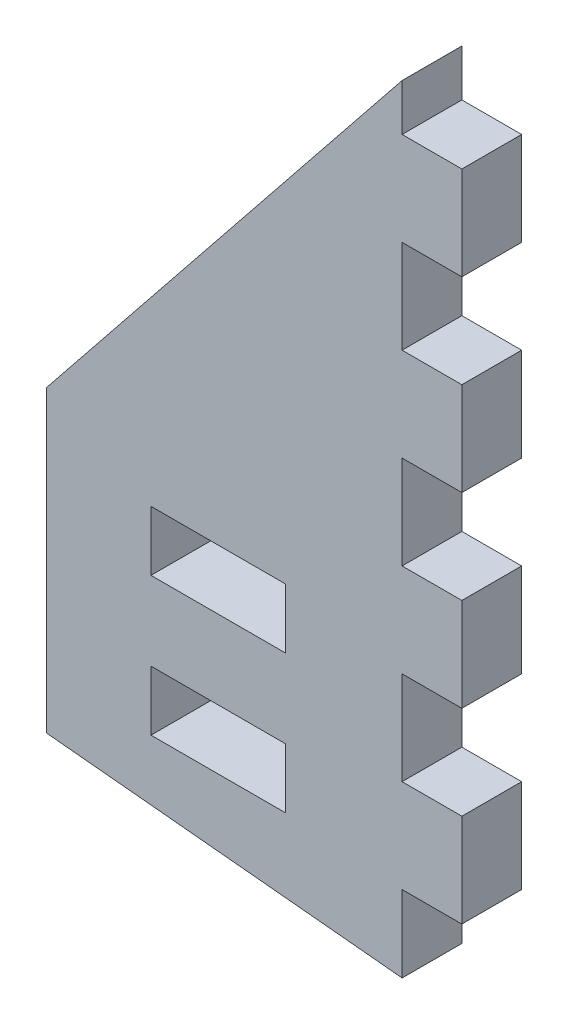
SolidWorks part; units mm, degrees
ref_plane "Piano frontale" through (0, 0, 0) normal (0, 0, 1) x (1, 0, 0)
ref_plane "Piano superiore" through (0, 0, 0) normal (0, 1, 0) x (1, 0, 0)
ref_plane "Piano destro" through (0, 0, 0) normal (1, 0, 0) x (0, 0, -1)
sketch "Schizzo1" plane through (0, 0, 0) normal (0, 0, 1) x (1, 0, 0)
  line L0 (-23.8, 20.3) -> (-23.8, 0.3)
  line L1 (-23.8, 0.3) -> (0, 0)
  line L2 (0, 0) -> (0, 50)
  line L3 (0, 50) -> (-23.8, 20.3)
  line L17 (-23.8, 0.3) -> (0, -2)
  line L18 (-16.8, 7.67) -> (-7.8, 7.67)
  line L19 (-16.8, 7.67) -> (-16.8, 3.67)
  line L20 (-16.8, 3.67) -> (-7.8, 3.67)
  line L21 (-7.8, 7.67) -> (-7.8, 3.67)
  line L22 (-16.8, 16.93) -> (-7.8, 16.93)
  line L23 (-16.8, 16.93) -> (-16.8, 12.93)
  line L24 (-16.8, 12.93) -> (-7.8, 12.93)
  line L25 (-7.8, 16.93) -> (-7.8, 12.93)
  line L26 (0, -2) -> (0, 0)
  point P2 (-16.8, 5.67)
  point P5 (-23.8, 10.3)
  point P11 (-7.8, 14.93)
  point P21 (-7.8, 5.67)
  dimension "D1" = 50
  dimension "D2" = 20
  dimension "D3" = 23.8
  dimension "D9" = 4
  dimension "D10" = 9
  dimension "D11" = 7
  dimension "D5" = 4
  dimension "D6" = 9.26
  dimension "D4" = 4.63
  dimension "D7" = 0.3
  dimension "D8" = 2
extrude "Estrusione-Estrusione1" add sketch "Schizzo1" along normal blind 4 contours L17 L26 L1 | L19 L18 L21 L20 | L23 L22 L25 L24
sketch "Schizzo2" plane through (0, 0, 4) normal (0, 0, 1) x (1, 0, 0)
  line L1 (0, 46.875) -> (4, 46.875)
  line L2 (0, 46.875) -> (0, 40.625)
  line L3 (0, 40.625) -> (4, 40.625)
  line L4 (4, 46.875) -> (4, 40.625)
  line L5 (0, -2) -> (0, 50) construction
  dimension "D1" = 6.25
  dimension "D2" = 4
  dimension "D3" = 3.125
extrude "Estrusione-Estrusione2" add sketch "Schizzo2" against normal blind 4
pattern_linear "Ripetizione a L1" count 4 spacing 12.5 along (0, -1, 0) of "Estrusione-Estrusione2"
equation "\"WFront\"= 140mm"
equation "\"HFront\"= 80mm"
equation "\"DFront\"= 4mm"
equation "\"WLeft\"= 50mm"
equation "\"HLeft\"= 80mm"
equation "\"DLeft\"= 4mm"
equation "\"WTop\"= 140mm"
equation "\"HTop\"= 50mm"
equation "\"DTop\"= 4mm"
equation "\"N_Denti_W\"= 10"
equation "\"N_Denti_H\"= 7"
equation "\"N_Denti_D\"= 4"
equation "\"HDistDenti\"= \"HFront\" / \"N_Denti_H\""
equation "\"WDistDenti\"= \"WFront\" / \"N_Denti_W\""
equation "\"DDistDenti\"= \"WLeft\" / \"N_Denti_D\""
equation "\"HDenti\"= \"HDistDenti\" / 2"
equation "\"WDenti\"= \"WDistDenti\" / 2"
equation "\"DDenti\"= \"DDistDenti\" / 2"
equation "\"WDisplay\"= 95mm"
equation "\"HDisplay\"= 61mm"
equation "\"CEnc\"= 7mm"
equation "\"Display_to_Enc_W\"= 11.5 + \"CEnc\" / 2"
equation "\"Display_to_Dx\"= 32mm"
equation "\"Display_to_Top\"= 10mm"
equation "\"Display_to_Enc_H\"= 24 + \"CEnc\" / 2"
equation "\"DMask\"= 3mm"
equation "\"D1@Estrusione-Estrusione1\"=\"DFront\""
equation "\"D1@Schizzo2\"=\"DDenti\""
equation "\"D2@Schizzo2\"=\"DFront\""
equation "\"D1@Estrusione-Estrusione2\"=\"DFront\""
equation "\"D1@Ripetizione a L1\"=\"N_Denti_D\""
equation "\"D3@Ripetizione a L1\"=\"DDistDenti\""
equation "\"D1@Schizzo1\"=\"WLeft\""
equation "\"D9@Schizzo1\"=\"DFront\""
equation "\"D7@Schizzo1\"=0.3"
equation "\"D3@Schizzo2\"=\"DDenti\"/2"
